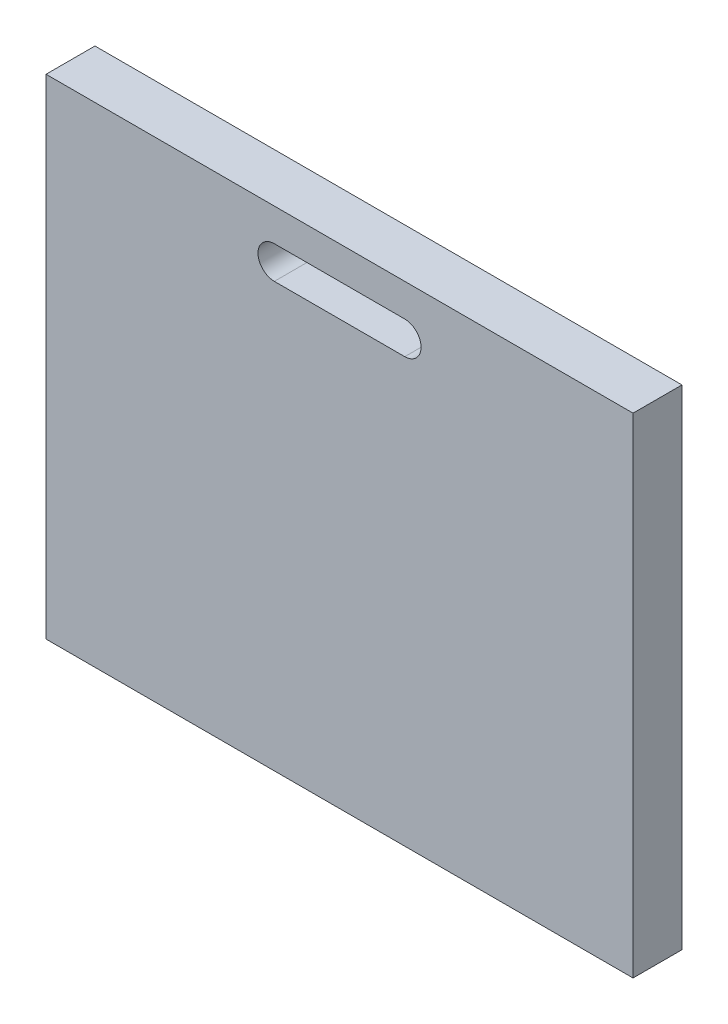
SolidWorks part; units mm, degrees
material "Pino"
ref_plane "Alzado" through (0, 0, 0) normal (0, 0, 1) x (1, 0, 0)
ref_plane "Planta" through (0, 0, 0) normal (0, 1, 0) x (1, 0, 0)
ref_plane "Vista lateral" through (0, 0, 0) normal (1, 0, 0) x (0, 0, -1)
sketch "Croquis1" plane through (0, 0, 0) normal (0, 0, 1) x (1, 0, 0)
  line L0 (-63.8456, 71.2852) -> (-63.8456, 56.2852) construction
  line L1 (-153.8456, 71.2852) -> (26.1544, 71.2852)
  line L2 (-153.8456, 71.2852) -> (-153.8456, -78.7148)
  line L3 (-153.8456, -78.7148) -> (26.1544, -78.7148)
  line L4 (26.1544, 71.2852) -> (26.1544, -78.7148)
  line L5 (-83.8456, 56.2852) -> (-43.8456, 56.2852) construction
  line L6 (-83.8456, 61.2852) -> (-43.8456, 61.2852)
  line L7 (-83.8456, 51.2852) -> (-43.8456, 51.2852)
  arc A0 (-83.8456, 61.2852) -> (-83.8456, 51.2852) centre (-83.8456, 56.2852) ccw
  arc A1 (-43.8456, 51.2852) -> (-43.8456, 61.2852) centre (-43.8456, 56.2852) ccw
  point P8 (-63.8456, 56.2852)
  dimension "D1" = 150
  dimension "D2" = 180
  dimension "D3" = 15
  dimension "D4" = 10
  dimension "D5" = 40
extrude "Saliente-Extruir1" add sketch "Croquis1" along normal blind 15
